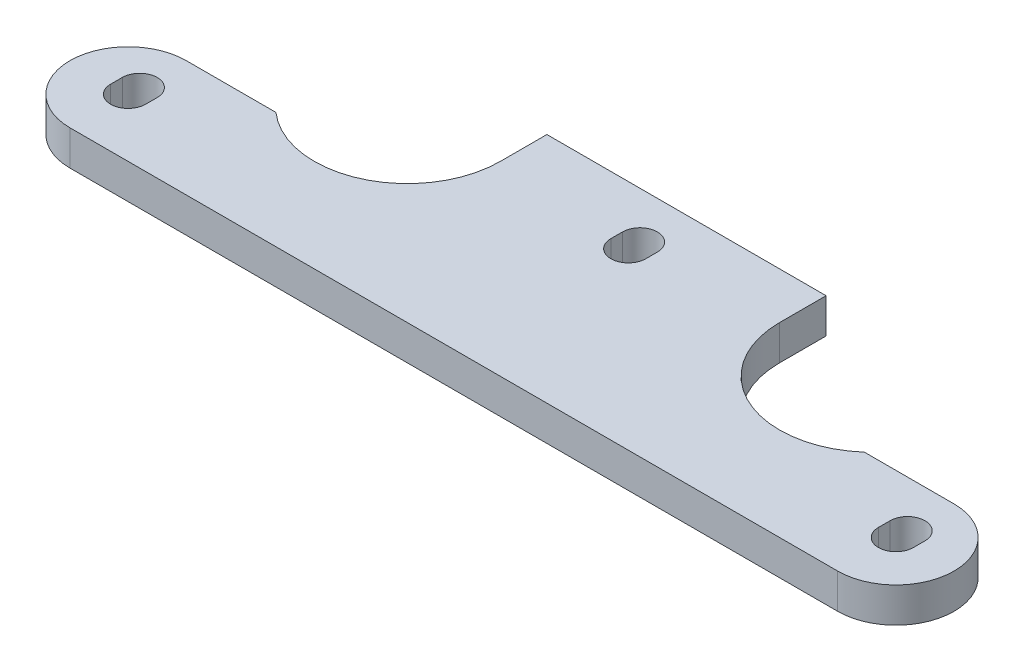
SolidWorks part; units mm, degrees
material "6061 Alloy"
ref_plane "Front Plane" through (0, 0, 0) normal (0, 0, 1) x (1, 0, 0)
ref_plane "Top Plane" through (0, 0, 0) normal (0, 1, 0) x (1, 0, 0)
ref_plane "Right Plane" through (0, 0, 0) normal (1, 0, 0) x (0, 0, -1)
sketch "Sketch1" plane through (0, 0, 0) normal (0, 1, 0) x (1, 0, 0)
  line L0 (0, 0) -> (-33, 0)
  line L1 (0, 0) -> (33, 0)
  line L2 (-33, 10) -> (-25.2915, 10)
  line L3 (12, 20) -> (-12, 20)
  line L4 (25.2915, 10) -> (33, 10)
  line L5 (-12, 20) -> (-12, 16)
  line L6 (12, 20) -> (12, 16)
  line L7 (-38, 5) -> (38, 5) construction
  arc A0 (-33, 0) -> (-33, 10) centre (-33, 5) cw
  arc A1 (33, 0) -> (33, 10) centre (33, 5) ccw
  arc A2 (-12, 16) -> (-25.2915, 10) centre (-20, 16) cw
  arc A3 (12, 16) -> (25.2915, 10) centre (20, 16) ccw
  dimension "D1" = 5
  dimension "D2" = 8
  dimension "D3" = 40
  dimension "D4" = 16
  dimension "D5" = 20
  dimension "D6" = 76
extrude "Boss-Extrude1" add sketch "Sketch1" along normal blind 3
sketch "Sketch2" plane through (0, 3, 0) normal (0, 1, 0) x (1, 0, 0)
  line L0 (-33, 5) -> (-33, 6) construction
  line L1 (-34.5, 5) -> (-34.5, 6)
  line L2 (-31.5, 5) -> (-31.5, 6)
  line L3 (33, 5) -> (33, 6) construction
  line L4 (31.5, 5) -> (31.5, 6)
  line L5 (34.5, 5) -> (34.5, 6)
  line L6 (0, 0) -> (0, 15) construction
  line L7 (0, 15) -> (0, 16) construction
  line L8 (-1.5, 15) -> (-1.5, 16)
  line L9 (1.5, 15) -> (1.5, 16)
  arc A0 (-34.5, 5) -> (-31.5, 5) centre (-33, 5) ccw
  arc A1 (-31.5, 6) -> (-34.5, 6) centre (-33, 6) ccw
  arc A2 (31.5, 5) -> (34.5, 5) centre (33, 5) ccw
  arc A3 (34.5, 6) -> (31.5, 6) centre (33, 6) ccw
  arc A4 (-1.5, 15) -> (1.5, 15) centre (0, 15) ccw
  arc A5 (1.5, 16) -> (-1.5, 16) centre (0, 16) ccw
  point P3 (-33, 5.5)
  point P8 (33, 5.5)
  point P20 (0, 15.5)
  dimension "D2" = 3
  dimension "D1" = 1
  dimension "D3" = 15
extrude "Cut-Extrude1" cut sketch "Sketch2" against normal through all
